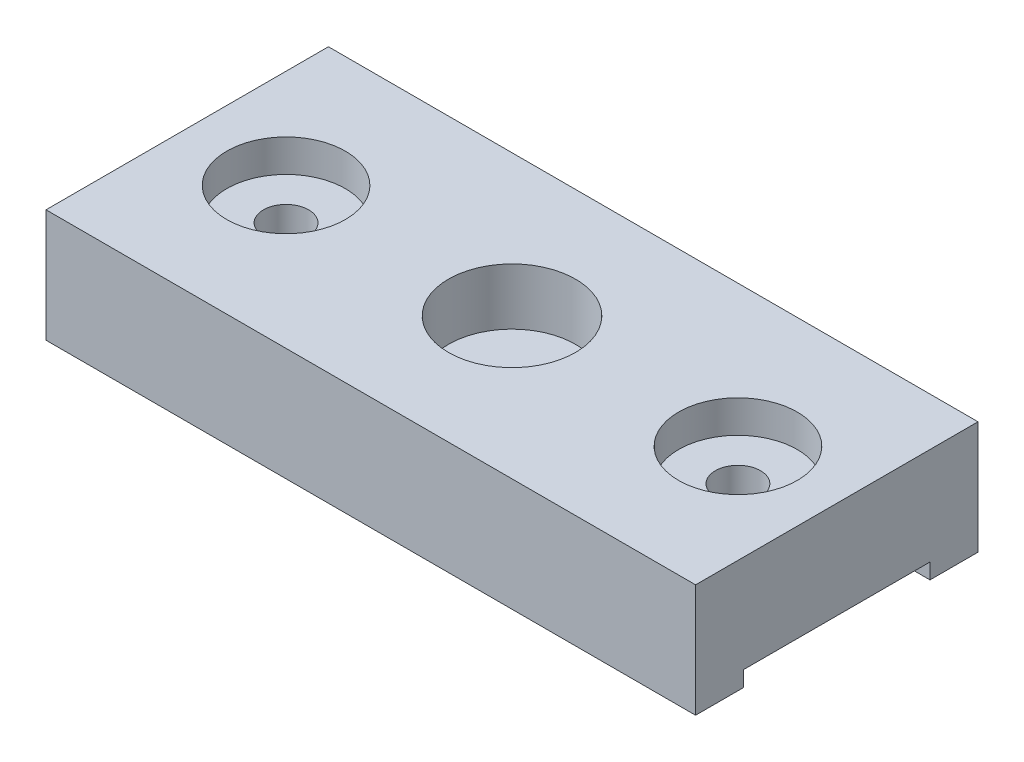
SolidWorks part; units mm, degrees
ref_plane "Piano frontale" through (0, 0, 0) normal (0, 0, 1) x (1, 0, 0)
ref_plane "Piano superiore" through (0, 0, 0) normal (0, 1, 0) x (1, 0, 0)
ref_plane "Piano destro" through (0, 0, 0) normal (1, 0, 0) x (0, 0, -1)
sketch "Sketch1" plane through (0, 0, 0) normal (0, 1, 0) x (1, 0, 0)
  line L0 (0, 0) -> (0, 20)
  line L1 (-23, -10) -> (23, -10)
  line L2 (-23, -10) -> (-23, 10)
  line L3 (-23, 10) -> (23, 10)
  line L5 (-23, -10) -> (23, 10) construction
  line L6 (-23, 10) -> (23, -10) construction
  line L7 (0, 20) -> (0, 22.5)
  line L8 (0, 22.5) -> (0, 27.5)
  line L9 (23, -10) -> (23, 10)
  line L10 (0, 0) -> (8, 0)
  line L11 (0, 0) -> (-8, 0)
  point P0 (0, 0)
extrude "Boss-Extrude1" add sketch "Sketch1" along normal blind 8
sketch "Sketch3" plane through (0, 8, 0) normal (0, 1, 0) x (1, 0, 0)
  circle A2 centre (0, 0) radius 4.5
extrude "Cut-Extrude2" cut sketch "Sketch3" against normal blind 4
sketch "Sketch4" plane through (0, 8, 0) normal (0, 1, 0) x (1, 0, 0)
  point P3 (8, 0)
  point P5 (-8, 0)
sketch "Sketch8" plane through (-23, 0, 0) normal (-1, 0, 0) x (0, 0, 1)
  line L0 (0, 0) -> (-6.6, 0)
  line L2 (10, 0) -> (-10, 0) construction
  line L3 (-6.6, 0) -> (-6.6, 1.1)
  line L4 (-6.6, 1.1) -> (6.6, 1.1)
  line L5 (6.6, 1.1) -> (6.6, 0)
  line L6 (0, 0) -> (6.6, 0)
extrude "Cut-Extrude3" cut sketch "Sketch8" against normal up to next
sketch "Sketch9" plane through (0, 8, 0) normal (0, 1, 0) x (1, 0, 0)
  line L0 (-8, 0) -> (-16, 0)
  line L1 (8, 0) -> (16, 0)
hole_wizard "CBORE for M3 Hex Head Machine Screw1" positions "Sketch10" profile "Sketch11" counterbore size "M3" standard "ANSI Metric" end condition up to next
sketch "Sketch10" plane through (0, 8, 0) normal (0, 1, 0) x (1, 0, 0)
  point P0 (-16, 0)
  point P3 (16, 0)
sketch "Sketch11" plane through (-16, 8, 0) normal (1, 0, 0) x (0, 0, 1)
  line L0 (0, 0) -> (0, 6.9)
  line L1 (0, 6.9) -> (1.6, 6.9)
  line L3 (1.6, 6.9) -> (1.6, 2.3)
  line L4 (1.6, 2.3) -> (4.2, 2.3)
  line L5 (4.2, 2.3) -> (4.2, 0)
  line L7 (4.2, 0) -> (0, 0)
  line L11 (0, -6.35) -> (0, 107.95) construction
  dimension "Thru Hole Dia." = 3.2
  dimension "Thru Hole Depth" = 6.9
  dimension "C'Bore Dia." = 8.4
  dimension "C'Bore Depth" = 2.3
